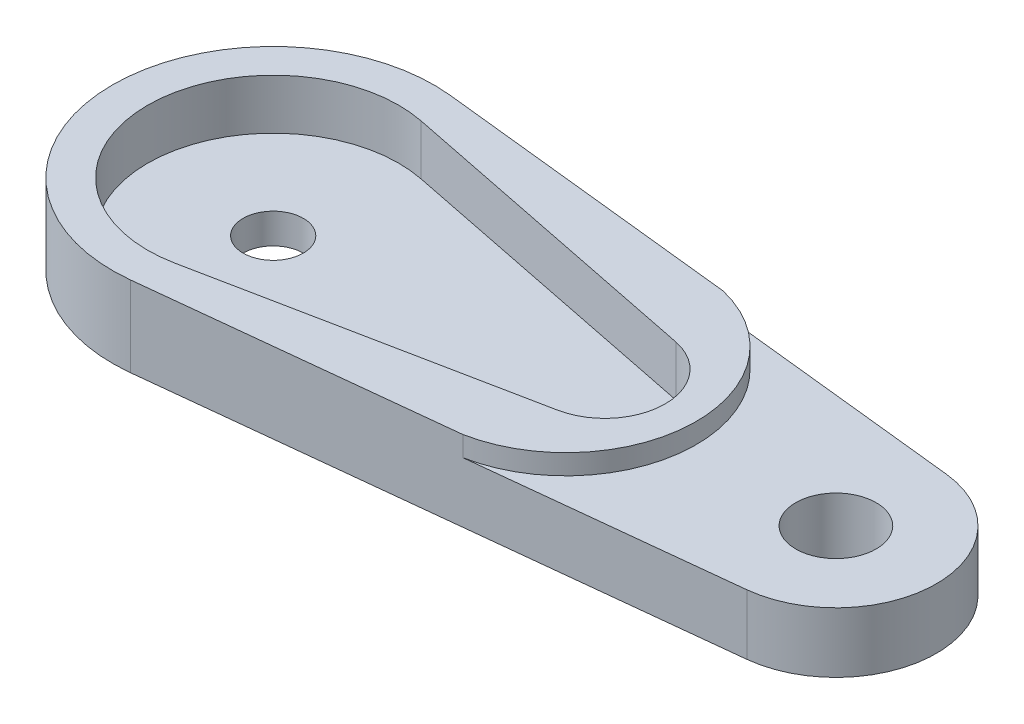
SolidWorks part; units mm, degrees
ref_plane "Front Plane" through (0, 0, 0) normal (0, 0, 1) x (1, 0, 0)
ref_plane "Top Plane" through (0, 0, 0) normal (0, 1, 0) x (1, 0, 0)
ref_plane "Right Plane" through (0, 0, 0) normal (1, 0, 0) x (0, 0, -1)
sketch "Sketch1" plane through (0, 0, 0) normal (0, 1, 0) x (1, 0, 0)
  line L0 (0.8571, 7.9539) -> (28.5357, 4.9712)
  line L1 (0.8571, -7.9539) -> (28.5357, -4.9712)
  line L2 (0, 0) -> (28, 0) construction
  circle A0 centre (0, 0) radius 8
  circle A1 centre (28, 0) radius 2
  circle A2 centre (28, 0) radius 5
  circle A3 centre (0, 0) radius 1.5
  dimension "D1" = 16
  dimension "D2" = 4
  dimension "D3" = 3
  dimension "D5" = 3
  dimension "D4" = 28
extrude "Boss-Extrude1" add sketch "Sketch1" along normal blind 4
sketch "Sketch2" plane through (0, 4, 0) normal (0, 1, 0) x (1, 0, 0)
  line L0 (0, 0) -> (16.5, 0) construction
  line L1 (1.2311, 6.1276) -> (17.0909, 2.9412)
  line L2 (1.2311, -6.1276) -> (17.0909, -2.9412)
  circle A0 centre (0, 0) radius 6.25
  circle A1 centre (16.5, 0) radius 3
  point P5 (1.3884, -6.0938)
  point P10 (24.1353, -8.6091)
  point P11 (16.9755, -2.9621)
  point P12 (17.0909, 2.9412)
  point P13 (1.1174, 6.1493)
  point P14 (1.2311, 6.1276)
  dimension "D1" = 12.5
  dimension "D2" = 6
  dimension "D3" = 16.5
extrude "Cut-Extrude1" cut sketch "Sketch2" against normal blind 2.5
sketch "Sketch3" plane through (0, 4, 0) normal (0, 1, 0) x (1, 0, 0)
  line L4 (28.5357, 4.9712) -> (0.8571, 7.9539)
  line L5 (0.8571, -7.9539) -> (28.5357, -4.9712)
  line L6 (28.5357, 4.9712) -> (0.8571, 7.9539)
  line L7 (0.8571, -7.9539) -> (28.5357, -4.9712)
  circle A2 centre (28, 0) radius 2 construction
  circle A3 centre (28, 0) radius 2
  arc A4 (28.5357, -4.9712) -> (28.5357, 4.9712) centre (28, 0) ccw
  arc A5 (0.8571, 7.9539) -> (0.8571, -7.9539) centre (0, 0) ccw
  arc A6 (28.5357, -4.9712) -> (28.5357, 4.9712) centre (28, 0) ccw
  arc A7 (0.8571, 7.9539) -> (0.8571, -7.9539) centre (0, 0) ccw
  arc A8 (14.4022, 6.4943) -> (14.6964, -6.4626) centre (14.5493, 0.0159) cw
  arc M9 (28.5357, -4.9712) -> (28.5357, 4.9712) centre (28, 0) ccw
  line M10 (28.5357, 4.9712) -> (0.8571, 7.9539)
  line M12 (0.8571, -7.9539) -> (28.5357, -4.9712)
  circle M13 centre (28, 0) radius 2
  dimension "D1" = 0
extrude "Cut-Extrude2" cut sketch "Sketch3" against normal blind 1 contours A8 M10 M12 M9 M13
